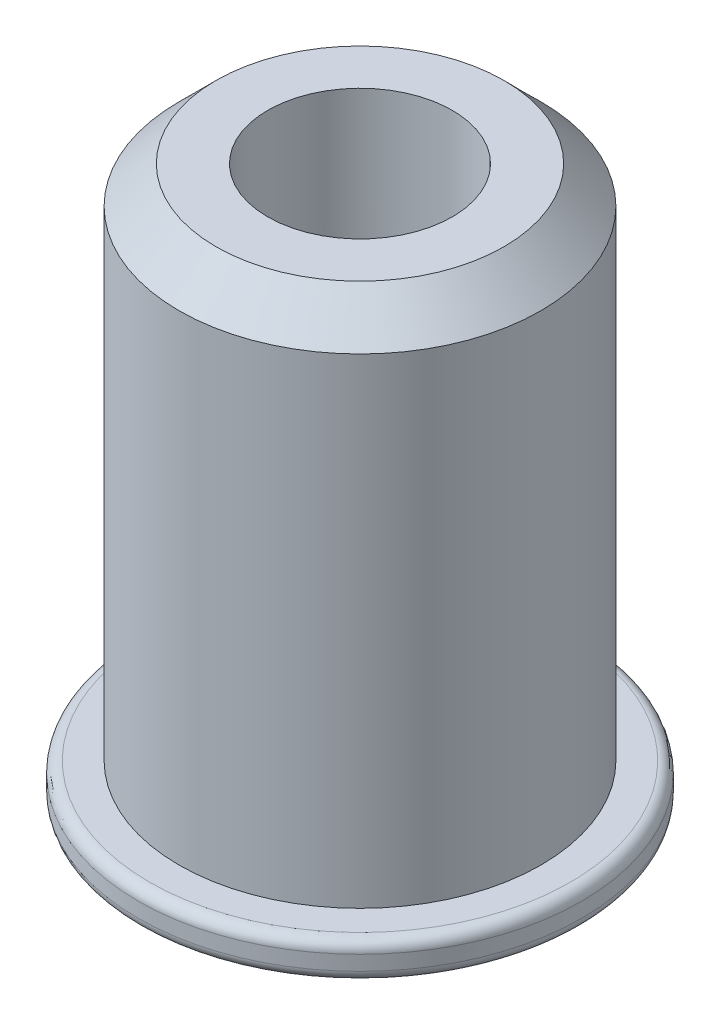
SolidWorks part; units mm, degrees
ref_plane "Plano frontal" through (0, 0, 0) normal (0, 0, 1) x (1, 0, 0)
ref_plane "Plano superior" through (0, 0, 0) normal (0, 1, 0) x (1, 0, 0)
ref_plane "Plano direito" through (0, 0, 0) normal (1, 0, 0) x (0, 0, -1)
sketch "Esboço1" plane through (0, 0, 0) normal (0, 1, 0) x (1, 0, 0)
  circle A0 centre (-26.7512, -11.3386) radius 3
  dimension "D1" = 6
extrude "Extrusão1" add sketch "Esboço1" along normal blind 0.5
sketch "Esboço2" plane through (0, 0.5, 0) normal (0, 1, 0) x (1, 0, 0)
  circle A0 centre (-26.7512, -11.3386) radius 2.45
  dimension "D1" = 4.9
extrude "Extrusão2" add sketch "Esboço2" along normal blind 7
chamfer "Chanfro1" distance 0.5 angle 45 1 edges at (-26.7512, 7.5, 13.7886)
sketch "Esboço3" plane through (0, 0, 0) normal (0, -1, 0) x (1, 0, 0)
  circle A0 centre (-26.7512, 11.3386) radius 1.95
  dimension "D1" = 3.9
extrude "Extrusão3" cut sketch "Esboço3" against normal blind 2
sketch "Esboço4" plane through (0, 7.5, 0) normal (0, 1, 0) x (1, 0, 0)
  circle A0 centre (-26.7512, -11.3386) radius 1.05
  dimension "D1" = 2.1
extrude "Extrusão4" cut sketch "Esboço4" against normal blind 10
hole_wizard "Furo roscado de M3x0.53" positions "3DSketch1" profile "Esboço5" tap size "M3x0.5" standard "Ansi Metric"
sketch3d "3DSketch1"
  line L0 (-26.7512, 2, 11.3386) -> (-26.7512, 7.5, 11.3386) construction
  point P0 (-26.7512, 7.5, 11.3386)
sketch "Esboço5" plane through (-26.7512, 7.5, 11.3386) normal (1, 0, 0) x (0, 0, 1)
  line L0 (0, 0) -> (0, 9.2511)
  line L1 (0, 9.2511) -> (1.25, 8.5)
  line L2 (1.25, 8.5) -> (1.25, 0)
  line L5 (1.25, 0) -> (0, 0)
  line L10 (0, 9.2511) -> (-1.25, 8.5) construction
  line L11 (0, -6.35) -> (0, 107.95) construction
  dimension "Tap Drill Dia." = 2.5
  dimension "Tap Drill Depth" = 8.5
  dimension "Drill Angle" = 118
cosmetic thread "Rosca de furo1" parameters "D1"=6, "D2"=3
fillet "Filete1" radius 0.15 3 edges at (-26.7512, 0, 9.3886) (-26.7512, 0.5, 14.3386) (-26.7512, 0, 14.3386)
